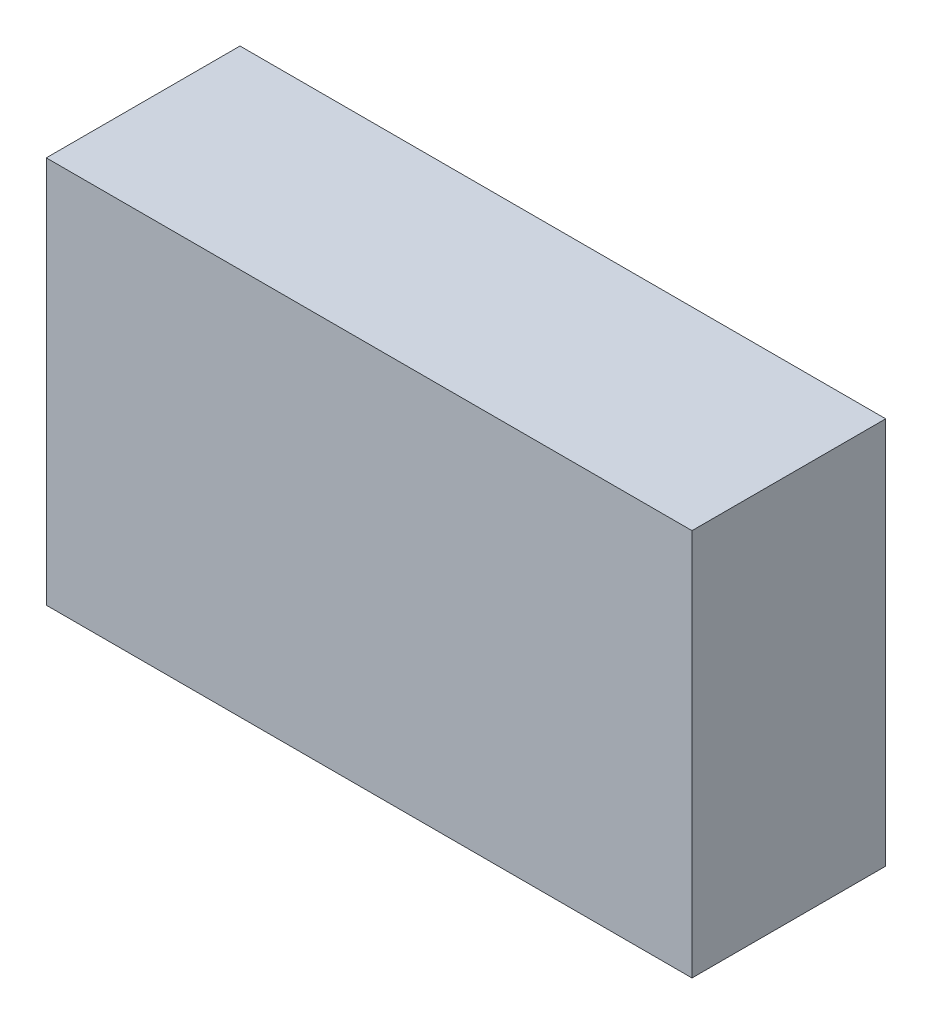
SolidWorks part; units mm, degrees
ref_plane "Front Plane" through (0, 0, 0) normal (0, 0, 1) x (1, 0, 0)
ref_plane "Top Plane" through (0, 0, 0) normal (0, 1, 0) x (1, 0, 0)
ref_plane "Right Plane" through (0, 0, 0) normal (1, 0, 0) x (0, 0, -1)
sketch "Sketch1" plane through (0, 0, 0) normal (0, 0, 1) x (1, 0, 0)
  line L1 (0, 0) -> (100, 0)
  line L2 (0, 0) -> (0, 60)
  line L3 (0, 60) -> (100, 60)
  line L4 (100, 0) -> (100, 60)
  dimension "D1" = 100
  dimension "D2" = 60
extrude "Base_Extrude" add sketch "Sketch1" along normal blind 30
equation "\"outer_length\" = 100mm"
equation "\"outer_width\" = 60mm"
equation "\"height\" = 30mm"
equation "\"D1@Sketch1\" = \"outer_length\""
equation "\"D2@Sketch1\" = \"outer_width\""
equation "\"D1@Base_Extrude\" = \"height\""
